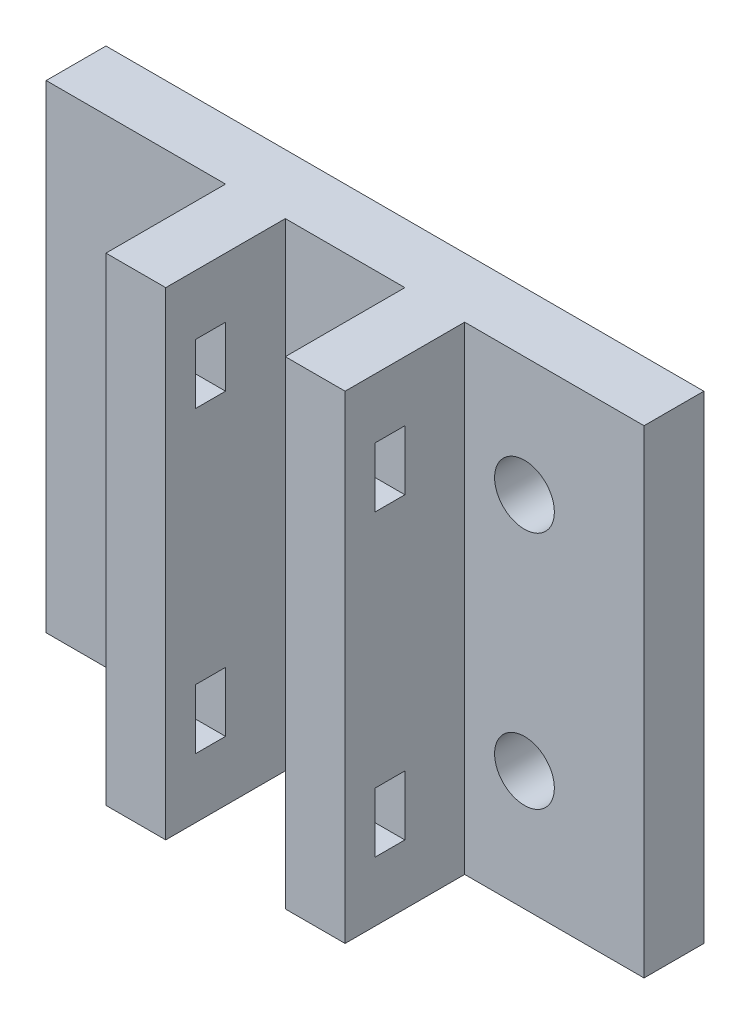
SolidWorks part; units mm, degrees
ref_plane "Front Plane" through (0, 0, 0) normal (0, 0, 1) x (1, 0, 0)
ref_plane "Top Plane" through (0, 0, 0) normal (0, 1, 0) x (1, 0, 0)
ref_plane "Right Plane" through (0, 0, 0) normal (1, 0, 0) x (0, 0, -1)
sketch "Sketch1" plane through (669.8418, 0, 0) normal (0, 0, 1) x (1, 0, 0)
  line L1 (-696.3103, 457.6379) -> (-646.3103, 457.6379)
  line L2 (-696.3103, 457.6379) -> (-696.3103, 417.6379)
  line L3 (-696.3103, 417.6379) -> (-646.3103, 417.6379)
  line L4 (-646.3103, 457.6379) -> (-646.3103, 417.6379)
  dimension "50" = 50
  dimension "D2" = 40
extrude "Boss-Extrude1" add sketch "Sketch1" along normal blind 10
sketch "Sketch5" plane through (23.5315, 0, 0) normal (1, 0, 0) x (0, 0, -1)
  line L0 (0, 417.6379) -> (0, 457.6379) construction
  line L1 (-8, 445.1379) -> (-2, 445.1379)
  line L2 (-8, 445.1379) -> (-8, 440.1379)
  line L3 (-8, 440.1379) -> (-2, 440.1379)
  line L4 (-2, 445.1379) -> (-2, 440.1379)
  line L5 (-8, 435.1379) -> (-2, 435.1379)
  line L6 (-8, 435.1379) -> (-8, 430.1379)
  line L7 (-8, 430.1379) -> (-2, 430.1379)
  line L8 (-2, 435.1379) -> (-2, 430.1379)
  line L9 (-10, 417.6379) -> (-10, 457.6379) construction
  line L10 (0, 437.6379) -> (-10, 437.6379)
  line L11 (-2, 440.1379) -> (-2, 437.6379)
  line L12 (-8, 435.1379) -> (-8, 437.6379)
  dimension "D1" = 5
  dimension "D2" = 2
  dimension "D3" = 2
  dimension "D4" = 2
  dimension "D5" = 2
  dimension "D6" = 5
  dimension "D7" = 5
extrude "Boss-Extrude3" add sketch "Sketch5" along normal blind 10 contours L4 L1 L2 L3 | L8 L5 L6 L7
sketch "Sketch6" plane through (669.8418, 445.1379, 0) normal (0, 1, 0) x (1, 0, 0)
  line L1 (-646.3103, -8) -> (-646.3103, -2) construction
  line L2 (-646.3103, -5) -> (-636.3103, -5) construction
  line L3 (-636.3103, -8) -> (-636.3103, -2) construction
  line L4 (-641.3103, -8) -> (-641.3103, -2) construction
  line L5 (-636.3103, -8) -> (-646.3103, -8) construction
  line L6 (-636.3103, -2) -> (-646.3103, -2) construction
  circle A1 centre (-641.3103, -5) radius 1.25
  dimension "D1" = 2.5
extrude "Cut-Extrude1" cut sketch "Sketch6" against normal blind 20
sketch "Sketch8" plane through (-26.4685, 0, 0) normal (-1, 0, 0) x (0, 0, 1)
  line L1 (0, 417.6379) -> (10, 417.6379)
  line L2 (0, 417.6379) -> (0, 457.6379)
  line L3 (0, 457.6379) -> (10, 457.6379)
  line L4 (10, 417.6379) -> (10, 457.6379)
extrude "Cut-Extrude2" cut sketch "Sketch8" against normal blind 25
mirror "Mirror1" about plane through (-1.4685, 0, 0) normal (1, 0, 0) of "Cut-Extrude1", "Boss-Extrude1", "Boss-Extrude3"
sketch "Sketch9" plane through (0, 435.1379, 0) normal (0, 1, 0) x (1, 0, 0)
  line L1 (23.5315, -8) -> (33.5315, -8)
  line L2 (23.5315, -8) -> (23.5315, -2)
  line L3 (23.5315, -2) -> (33.5315, -2)
  line L4 (33.5315, -8) -> (33.5315, -2)
  circle A0 centre (28.5315, -5) radius 1.9309
sketch "Sketch12" plane through (0, 457.6379, 0) normal (0, 1, 0) x (1, 0, 0)
  line L0 (23.5315, 0) -> (-26.4685, 0) construction
  line L1 (-3.9685, -2.5) -> (1.0315, -2.5)
  line L2 (-3.9685, -2.5) -> (-3.9685, -7.5)
  line L3 (-3.9685, -7.5) -> (1.0315, -7.5)
  line L4 (1.0315, -2.5) -> (1.0315, -7.5)
  line L5 (23.5315, -10) -> (-26.4685, -10) construction
  line L6 (23.5315, -10) -> (23.5315, 0) construction
  line L7 (-26.4685, -10) -> (-26.4685, 0) construction
  dimension "D1" = 2.5
  dimension "D2" = 2.5
  dimension "D3" = 22.5
  dimension "D4" = 22.5
extrude "Boss-Extrude5" add sketch "Sketch12" along normal blind 10
sketch "Sketch13" plane through (1.0315, 0, 0) normal (1, 0, 0) x (0, 0, -1)
  line L0 (-5, 467.6379) -> (-5, 457.6379) construction
  line L1 (-7.5, 467.6379) -> (-2.5, 467.6379) construction
  line L2 (-7.5, 457.6379) -> (-2.5, 457.6379) construction
  line L3 (-7.5, 462.6379) -> (-2.5, 462.6379) construction
  line L4 (-7.5, 467.6379) -> (-7.5, 457.6379) construction
  line L5 (-2.5, 467.6379) -> (-2.5, 457.6379) construction
  circle A1 centre (-5, 462.6379) radius 1.25
  dimension "D1" = 2.5
extrude "Cut-Extrude4" cut sketch "Sketch13" against normal blind 10
sketch "Sketch14" plane through (0, 0, 10) normal (0, 0, 1) x (1, 0, 0)
  line L0 (23.5315, 457.6379) -> (-26.4685, 457.6379) construction
  line L1 (23.5315, 417.6379) -> (23.5315, 457.6379) construction
  line L2 (-26.4685, 417.6379) -> (-26.4685, 457.6379) construction
  line L3 (-26.4685, 417.6379) -> (23.5315, 417.6379) construction
  circle A0 centre (-16.4685, 447.6379) radius 2.5
  circle A1 centre (-16.4685, 427.6379) radius 2.5
  circle A2 centre (13.5315, 447.6379) radius 2.5
  circle A3 centre (13.5315, 427.6379) radius 2.5
  dimension "D1" = 5
  dimension "D4" = 10
  dimension "D2" = 10
  dimension "D3" = 10
  dimension "D5" = 10
extrude "Cut-Extrude5" cut sketch "Sketch14" against normal blind 10
sketch "Sketch15" plane through (0, 445.1379, 0) normal (0, 1, 0) x (1, 0, 0)
  line L0 (28.5315, -2) -> (33.5315, -2)
  line L1 (28.5315, -8) -> (33.5315, -8)
  circle A0 centre (28.5315, -5) radius 3
  line M3 (23.5315, -8) -> (33.5315, -8)
  line M4 (33.5315, -8) -> (33.5315, -2)
  line M5 (33.5315, -2) -> (23.5315, -2)
extrude "Cut-Extrude6" cut sketch "Sketch15" against normal blind 22 contours A0 M3 M4 M5
sketch "Sketch17" plane through (0, 445.1379, 0) normal (0, 1, 0) x (1, 0, 0)
  line L0 (-31.4685, -8) -> (-36.4685, -8)
  line L1 (-36.4685, -8) -> (-36.4685, -2)
  line L2 (-36.4685, -2) -> (-31.4685, -2)
  circle A0 centre (-31.4685, -5) radius 3
  line M3 (-26.4685, -2) -> (-36.4685, -2)
  line M4 (-36.4685, -2) -> (-36.4685, -8)
  line M5 (-36.4685, -8) -> (-26.4685, -8)
extrude "Cut-Extrude7" cut sketch "Sketch17" against normal blind 30 contours A0 M3 M4 M5
sketch "Sketch18" plane through (1.0315, 0, 0) normal (1, 0, 0) x (0, 0, -1)
  line L0 (-7.5, 462.6379) -> (-7.5, 467.6379)
  line L1 (-7.5, 467.6379) -> (-2.5, 467.6379)
  line L2 (-2.5, 467.6379) -> (-2.5, 462.6379)
  circle A0 centre (-5, 462.6379) radius 2.5
  line M4 (-2.5, 457.6379) -> (-2.5, 467.6379)
  line M5 (-2.5, 467.6379) -> (-7.5, 467.6379)
  line M6 (-7.5, 467.6379) -> (-7.5, 457.6379)
extrude "Cut-Extrude8" cut sketch "Sketch18" against normal blind 30 contours A0 M4 M5 M6
scale "Scale1" bodies to scale 115 scale about centroid uniform scaling yes scale factor 2
sketch "Sketch19" plane through (0, 0, 15) normal (0, 0, 1) x (1, 0, 0)
  line L1 (-51.4685, 397.4653) -> (48.5315, 397.4653)
  line L2 (-51.4685, 397.4653) -> (-51.4685, 477.4653)
  line L3 (-51.4685, 477.4653) -> (48.5315, 477.4653)
  line L4 (48.5315, 397.4653) -> (48.5315, 477.4653)
  line L5 (-84.1379, 502.292) -> (88.4788, 502.292)
  line L6 (-84.1379, 502.292) -> (-84.1379, 372.9553)
  line L7 (-84.1379, 372.9553) -> (88.4788, 372.9553)
  line L8 (88.4788, 502.292) -> (88.4788, 372.9553)
extrude "Cut-Extrude9" cut sketch "Sketch19" against normal blind 20
sketch "Sketch20" plane through (0, 0, 15) normal (0, 0, 1) x (1, 0, 0)
  line L1 (-51.4685, 477.4653) -> (48.5315, 477.4653)
  line L2 (-51.4685, 477.4653) -> (-51.4685, 397.4653)
  line L3 (-51.4685, 397.4653) -> (48.5315, 397.4653)
  line L4 (48.5315, 477.4653) -> (48.5315, 397.4653)
extrude "Cut-Extrude10" cut sketch "Sketch20" against normal blind 10
sketch "Sketch21" plane through (0, 0, 5) normal (0, 0, 1) x (1, 0, 0)
  line L0 (48.5315, 477.4653) -> (-51.4685, 477.4653) construction
  line L1 (-21.4685, 477.4653) -> (-11.4685, 477.4653)
  line L2 (-21.4685, 477.4653) -> (-21.4685, 397.4653)
  line L3 (-21.4685, 397.4653) -> (-11.4685, 397.4653)
  line L4 (-11.4685, 477.4653) -> (-11.4685, 397.4653)
  line L5 (-51.4685, 397.4653) -> (48.5315, 397.4653) construction
  line L6 (-1.4685, 477.4653) -> (-1.4685, 397.4653)
  line L7 (8.5315, 397.4653) -> (18.5315, 397.4653)
  line L8 (8.5315, 397.4653) -> (8.5315, 477.4653)
  line L9 (8.5315, 477.4653) -> (18.5315, 477.4653)
  line L10 (18.5315, 397.4653) -> (18.5315, 477.4653)
  line L11 (-11.4685, 464.6195) -> (-1.4685, 464.6195)
  line L12 (-1.4685, 471.5889) -> (8.5315, 471.5889)
  line M12 (-51.4685, 397.4653) -> (48.5315, 397.4653)
  line M14 (48.5315, 477.4653) -> (-51.4685, 477.4653)
  dimension "D1" = 10
  dimension "D2" = 10
  dimension "D3" = 20
extrude "Boss-Extrude6" add sketch "Sketch21" along normal blind 20 contours L4 L2 M14 M12 | L10 L8 M12 M14
sketch "Sketch22" plane through (-21.4685, 0, 0) normal (-1, 0, 0) x (0, 0, 1)
  line L0 (25, 477.4653) -> (5, 477.4653) construction
  line L1 (20, 467.4653) -> (15, 467.4653)
  line L2 (20, 467.4653) -> (20, 457.4653)
  line L3 (20, 457.4653) -> (15, 457.4653)
  line L4 (15, 467.4653) -> (15, 457.4653)
  line L5 (20, 417.4653) -> (15, 417.4653)
  line L6 (20, 417.4653) -> (20, 407.4653)
  line L7 (20, 407.4653) -> (15, 407.4653)
  line L8 (15, 417.4653) -> (15, 407.4653)
  line L9 (25, 477.4653) -> (25, 397.4653) construction
  line L10 (25, 397.4653) -> (5, 397.4653) construction
  dimension "D1" = 10
  dimension "D2" = 5
  dimension "D3" = 10
  dimension "D4" = 5
  dimension "D5" = 5
  dimension "D6" = 10
  dimension "D7" = 10
  dimension "D8" = 5
extrude "Cut-Extrude11" cut sketch "Sketch22" against normal blind 50
